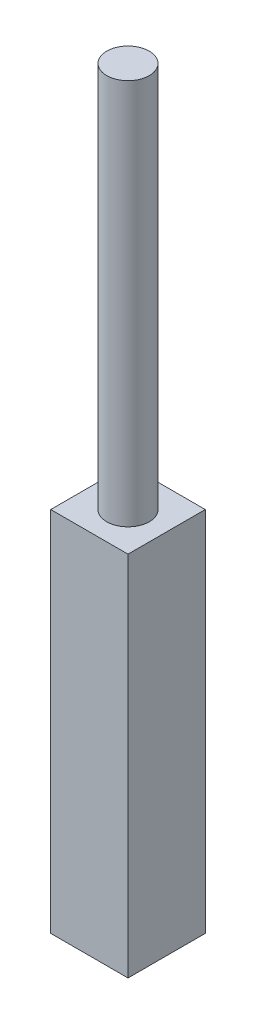
SolidWorks part; units mm, degrees
ref_plane "Front Plane" through (0, 0, 0) normal (0, 0, 1) x (1, 0, 0)
ref_plane "Top Plane" through (0, 0, 0) normal (0, 1, 0) x (1, 0, 0)
ref_plane "Right Plane" through (0, 0, 0) normal (1, 0, 0) x (0, 0, -1)
sketch "Sketch1" plane through (0, 0, 0) normal (0, 1, 0) x (1, 0, 0)
  line L1 (-1.27, -1.27) -> (1.27, -1.27)
  line L2 (-1.27, -1.27) -> (-1.27, 1.27)
  line L3 (-1.27, 1.27) -> (1.27, 1.27)
  line L4 (1.27, -1.27) -> (1.27, 1.27)
  line L5 (-1.27, -1.27) -> (1.27, 1.27) construction
  line L6 (-1.27, 1.27) -> (1.27, -1.27) construction
  point P0 (0, 0)
  dimension "D1" = 2.54
  dimension "D2" = 2.54
extrude "Boss-Extrude1" add sketch "Sketch1" along normal blind 12.065
sketch "Sketch2" plane through (0, 12.065, 0) normal (0, 1, 0) x (1, 0, 0)
  circle A0 centre (0, 0) radius 0.6985
  dimension "D1" = 1.397
extrude "Boss-Extrude2" add sketch "Sketch2" along normal blind 12.7
